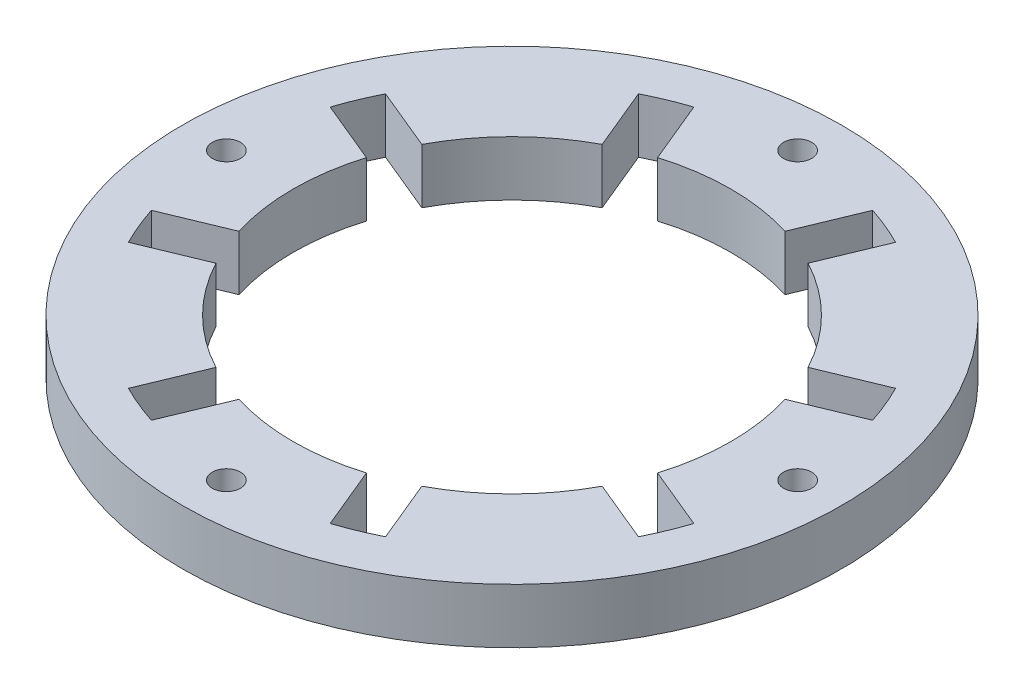
SolidWorks part; units mm, degrees
material "Acrylic (Medium-high impact)"
ref_plane "Front Plane" through (0, 0, 0) normal (0, 0, 1) x (1, 0, 0)
ref_plane "Top Plane" through (0, 0, 0) normal (0, 1, 0) x (1, 0, 0)
ref_plane "Right Plane" through (0, 0, 0) normal (1, 0, 0) x (0, 0, -1)
sketch "Sketch1" plane through (0, 0, 0) normal (0, 1, 0) x (1, 0, 0)
  line L0 (22.3249, -11.8991) -> (24.2, -7.3721) construction
  line L1 (0, 0) -> (23.2624, -9.6356) construction
  line L13 (29.4848, -14.8649) -> (22.3249, -11.8991)
  line L17 (24.2, -7.3721) -> (31.36, -10.3379)
  line L18 (0, 0) -> (27.7195, 0) construction
  line L23 (11.8991, -22.3249) -> (14.8649, -29.4848)
  line L24 (10.3379, -31.36) -> (7.3721, -24.2)
  line L29 (-7.3721, -24.2) -> (-10.3379, -31.36)
  line L30 (-14.8649, -29.4848) -> (-11.8991, -22.3249)
  line L35 (-22.3249, -11.8991) -> (-29.4848, -14.8649)
  line L36 (-31.36, -10.3379) -> (-24.2, -7.3721)
  line L41 (-24.2, 7.3721) -> (-31.36, 10.3379)
  line L42 (-29.4848, 14.8649) -> (-22.3249, 11.8991)
  line L47 (-11.8991, 22.3249) -> (-14.8649, 29.4848)
  line L48 (-10.3379, 31.36) -> (-7.3721, 24.2)
  line L53 (7.3721, 24.2) -> (10.3379, 31.36)
  line L54 (14.8649, 29.4848) -> (11.8991, 22.3249)
  line L59 (22.3249, 11.8991) -> (29.4848, 14.8649)
  line L60 (31.36, 10.3379) -> (24.2, 7.3721)
  circle A0 centre (0, 0) radius 38.1
  circle A1 centre (0, 33.02) radius 1.6256
  circle A2 centre (33.02, 0) radius 1.6256
  circle A3 centre (0, -33.02) radius 1.6256
  circle A4 centre (-33.02, 0) radius 1.6256
  arc A5 (-24.2, 7.3721) -> (-24.2, -7.3721) centre (0, 0) ccw
  arc A6 (-22.3249, -11.8991) -> (-11.8991, -22.3249) centre (0, 0) ccw
  arc A7 (24.2, -7.3721) -> (24.2, 7.3721) centre (0, 0) ccw
  circle A8 centre (0, 33.02) radius 1.6256 construction
  arc A10 (29.4848, -14.8649) -> (31.36, -10.3379) centre (0, 0) ccw
  arc A11 (-11.8991, 22.3249) -> (-22.3249, 11.8991) centre (0, 0) ccw
  arc A12 (10.3379, -31.36) -> (14.8649, -29.4848) centre (0, 0) ccw
  arc A13 (7.3721, 24.2) -> (-7.3721, 24.2) centre (0, 0) ccw
  arc A14 (-14.8649, -29.4848) -> (-10.3379, -31.36) centre (0, 0) ccw
  arc A15 (22.3249, 11.8991) -> (11.8991, 22.3249) centre (0, 0) ccw
  arc A16 (-31.36, -10.3379) -> (-29.4848, -14.8649) centre (0, 0) ccw
  arc A18 (-29.4848, 14.8649) -> (-31.36, 10.3379) centre (0, 0) ccw
  arc A20 (-10.3379, 31.36) -> (-14.8649, 29.4848) centre (0, 0) ccw
  arc A22 (14.8649, 29.4848) -> (10.3379, 31.36) centre (0, 0) ccw
  arc A24 (31.36, 10.3379) -> (29.4848, 14.8649) centre (0, 0) ccw
  arc A25 (11.8991, -22.3249) -> (22.3249, -11.8991) centre (0, 0) ccw
  arc A26 (-7.3721, -24.2) -> (7.3721, -24.2) centre (0, 0) ccw
  point P14 (0, 0)
  point P31 (0, 0)
  point P97 (0, 0)
  dimension "D1" = 76.2
  dimension "D6" = 22.5
  dimension "D4" = 33.02
  dimension "D5" = 7.7499
  dimension "D8" = 4.9
  dimension "D2" = 4
  dimension "D12" = 8
extrude "Boss-Extrude1" add sketch "Sketch1" along normal blind 6.35
